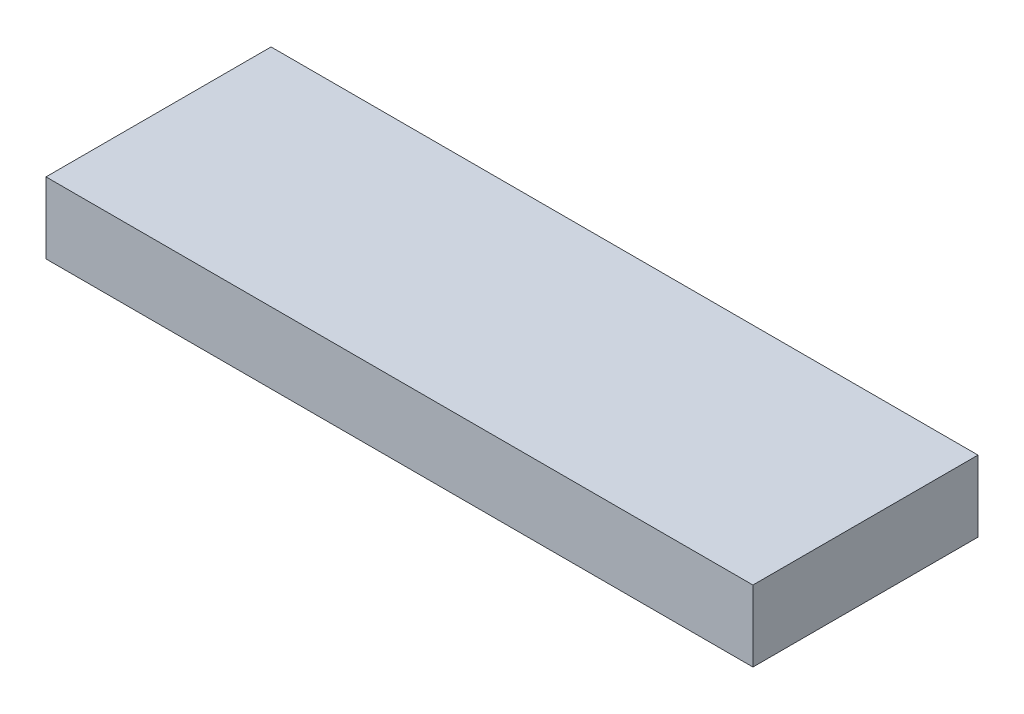
SolidWorks part; units mm, degrees
material "MDF"
ref_plane "Front Plane" through (0, 0, 0) normal (0, 0, 1) x (1, 0, 0)
ref_plane "Top Plane" through (0, 0, 0) normal (0, 1, 0) x (1, 0, 0)
ref_plane "Right Plane" through (0, 0, 0) normal (1, 0, 0) x (0, 0, -1)
sketch "Sketch1" plane through (0, 0, 0) normal (0, 0, 1) x (1, 0, 0)
  line L0 (-94.7388, -19.05) -> (-94.7388, -298.45) construction
  line L1 (-94.7388, -282.575) -> (94.7388, -282.575)
  line L2 (-94.7388, -282.575) -> (-94.7388, -263.525)
  line L3 (-94.7388, -263.525) -> (94.7388, -263.525)
  line L4 (94.7388, -282.575) -> (94.7388, -263.525)
  line L5 (94.7388, -19.05) -> (94.7388, -298.45) construction
  dimension "D1" = 19.05
  dimension "D2" = 3.175
extrude "Boss-Extrude1" add sketch "Sketch1" along normal up to surface (60.325 mm away)
